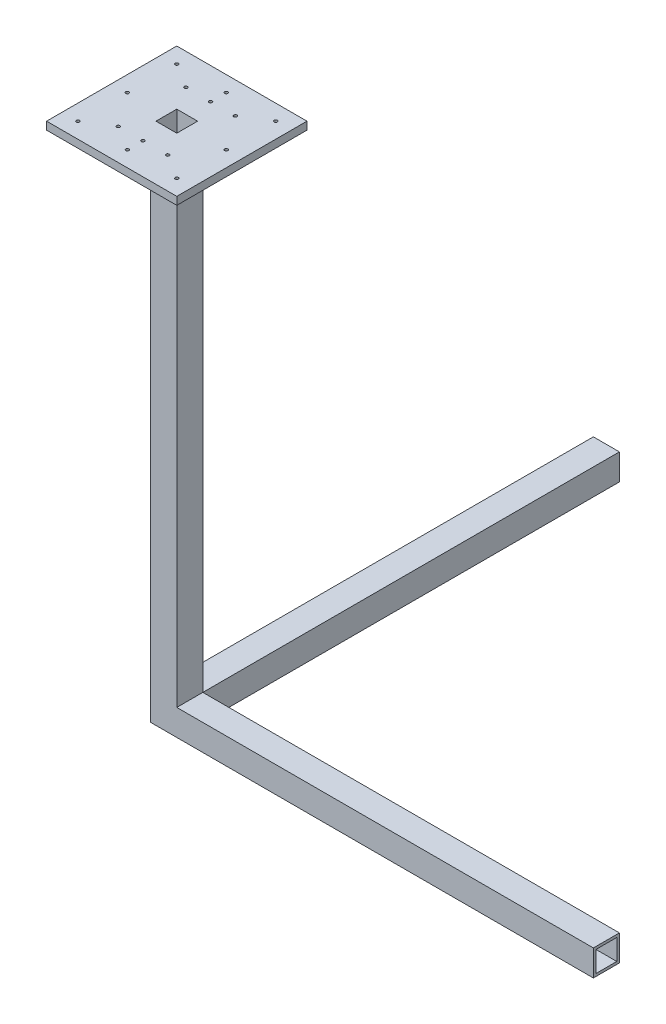
SolidWorks part; units mm, degrees
material "6061 Alloy"
ref_plane "Front Plane" through (0, 0, 0) normal (0, 0, 1) x (1, 0, 0)
ref_plane "Top Plane" through (0, 0, 0) normal (0, 1, 0) x (1, 0, 0)
ref_plane "Right Plane" through (0, 0, 0) normal (1, 0, 0) x (0, 0, -1)
sketch "Sketch1" plane through (0, 0, 0) normal (0, 1, 0) x (1, 0, 0)
  line L1 (0, 0) -> (25, 0)
  line L2 (0, 0) -> (0, 25)
  line L3 (0, 25) -> (25, 25)
  line L4 (25, 0) -> (25, 25)
  line L5 (2.5, 2.5) -> (22.5, 2.5)
  line L6 (2.5, 2.5) -> (2.5, 22.5)
  line L7 (2.5, 22.5) -> (22.5, 22.5)
  line L8 (22.5, 2.5) -> (22.5, 22.5)
  dimension "D1" = 2.5
  dimension "D2" = 2.5
  dimension "D3" = 2.5
  dimension "D4" = 2.5
  dimension "D5" = 25
  dimension "D6" = 25
extrude "Boss-Extrude1" add sketch "Sketch1" along normal blind 500
sketch "Sketch2" plane through (0, 500, 0) normal (0, 1, 0) x (1, 0, 0)
  line L1 (25, 0) -> (0, 0)
  line L2 (25, 0) -> (25, 25)
  line L3 (25, 25) -> (0, 25)
  line L4 (0, 0) -> (0, 25)
  line L5 (75, -50) -> (-50, -50)
  line L6 (75, -50) -> (75, 75)
  line L7 (75, 75) -> (-50, 75)
  line L8 (-50, -50) -> (-50, 75)
  dimension "D1" = 50
  dimension "D2" = 50
  dimension "D3" = 50
  dimension "D4" = 50
extrude "Boss-Extrude2" add sketch "Sketch2" against normal blind 7.5
hole_wizard "Ø3.0mm Dowel Hole1" positions "Sketch6" profile "Sketch4" hole size "Ø3.0" standard "ISO" end condition through all
sketch "Sketch6" plane through (0, 500, 0) normal (0, 1, 0) x (1, 0, 0)
  line L0 (-50, 60) -> (75, 60) construction
  line L1 (-50, 75) -> (-50, -50) construction
  line L2 (75, -50) -> (75, 75) construction
  line L6 (75, 12.5) -> (-50, 12.5) construction
  line L8 (12.5, 75) -> (12.5, -50) construction
  line L9 (75, 75) -> (-50, 75) construction
  line L10 (-50, -50) -> (75, -50) construction
  line L12 (-50, 45) -> (75, 45) construction
  line L14 (-35, 75) -> (-35, -50) construction
  line L18 (75, -35) -> (-50, -35) construction
  line L19 (-50, -20) -> (75, -20) construction
  line L21 (60, 75) -> (60, -50) construction
  point P0 (-35, 60)
  point P2 (12.5, 60)
  point P4 (60, 60)
  point P6 (60, 12.5)
  point P8 (60, -35)
  point P10 (12.5, -35)
  point P12 (-35, -35)
  point P14 (-35, 12.5)
  point P16 (12.5, 45)
  point P18 (12.5, -20)
  point P20 (-11.25, 45)
  point P22 (36.25, 45)
  point P24 (-11.25, -20)
  point P26 (36.25, -20)
  dimension "D1" = 15
  dimension "1.5" = 15
  dimension "D2" = 15
  dimension "D3" = 15
  dimension "D4" = 23.75
  dimension "D5" = 23.75
  dimension "D6" = 15
  dimension "D7" = 23.75
  dimension "D8" = 23.75
  dimension "D9" = 15
sketch "Sketch4" plane through (-35, 500, -60) normal (1, 0, 0) x (0, 0, 1)
  line L0 (0, 0) -> (0, 500)
  line L1 (0, 500) -> (1.5, 500)
  line L2 (1.5, 500) -> (1.5, 0)
  line L5 (1.5, 0) -> (0, 0)
  line L11 (0, -6.35) -> (0, 107.95) construction
  dimension "Thru Hole Dia." = 3
  dimension "Thru Hole Depth" = 500
sketch "Sketch7" plane through (0, 0, -25) normal (0, 0, -1) x (-1, 0, 0)
  line L0 (-25, 492.5) -> (-25, 0) construction
  line L5 (0, 0) -> (-25, 0)
  line L6 (0, 0) -> (0, 25)
  line L7 (0, 25) -> (-25, 25)
  line L8 (-25, 0) -> (-25, 25)
  line L10 (-2.5, 2.5) -> (-22.5, 2.5)
  line L11 (-2.5, 2.5) -> (-2.5, 22.5)
  line L12 (-2.5, 22.5) -> (-22.5, 22.5)
  line L13 (-22.5, 2.5) -> (-22.5, 22.5)
  dimension "D1" = 25
  dimension "D2" = 2.5
  dimension "D3" = 2.5
  dimension "D4" = 2.5
  dimension "D5" = 2.5
extrude "Boss-Extrude3" add sketch "Sketch7" along normal blind 400
sketch "Sketch8" plane through (25, 0, 0) normal (1, 0, 0) x (0, 0, -1)
  line L1 (25, 25) -> (0, 25)
  line L2 (25, 25) -> (25, 0)
  line L3 (25, 0) -> (0, 0)
  line L4 (0, 25) -> (0, 0)
  line L5 (22.5, 22.5) -> (2.5, 22.5)
  line L6 (22.5, 22.5) -> (22.5, 2.5)
  line L7 (22.5, 2.5) -> (2.5, 2.5)
  line L8 (2.5, 22.5) -> (2.5, 2.5)
  dimension "D1" = 2.5
  dimension "D2" = 2.5
  dimension "D3" = 2.5
  dimension "D4" = 2.5
extrude "Boss-Extrude4" add sketch "Sketch8" along normal blind 400
